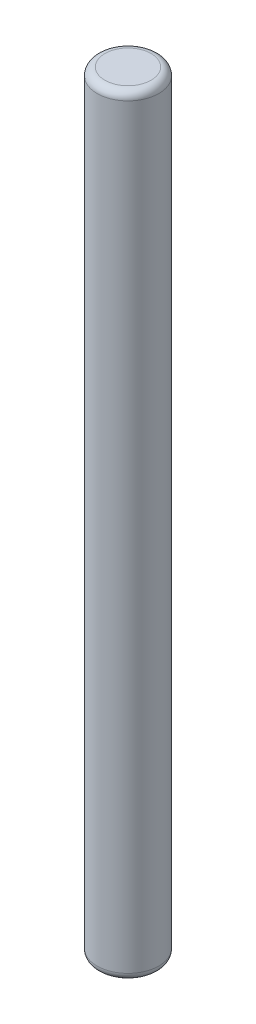
SolidWorks part; units mm, degrees
ref_plane "前视基准面" through (0, 0, 0) normal (0, 0, 1) x (1, 0, 0)
ref_plane "上视基准面" through (0, 0, 0) normal (0, 1, 0) x (1, 0, 0)
ref_plane "右视基准面" through (0, 0, 0) normal (1, 0, 0) x (0, 0, -1)
sketch "草图1" plane through (0, 0, 0) normal (0, 1, 0) x (1, 0, 0)
  circle A0 centre (0, 0) radius 2
  dimension "D1" = 4
extrude "凸台-拉伸1" add sketch "草图1" along normal blind 50
fillet "圆角1" radius 0.5 2 edges at (0, 0, 2) (0, 50, 2)
